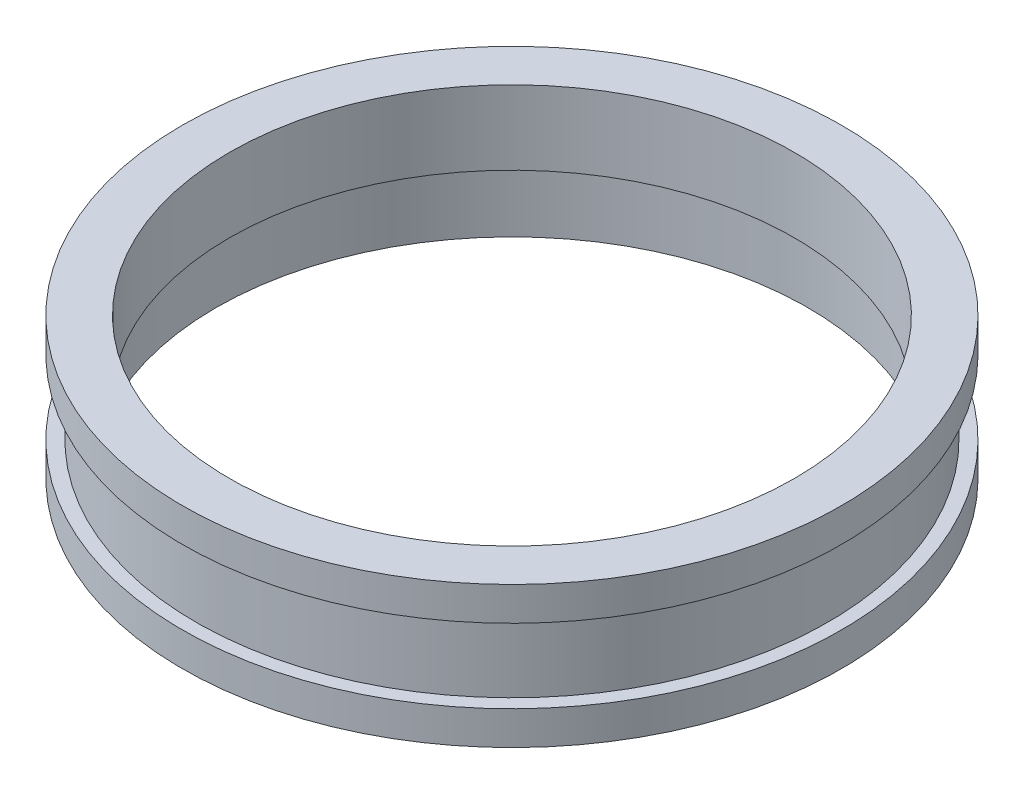
SolidWorks part; units mm, degrees
ref_plane "Front Plane" through (0, 0, 0) normal (0, 0, 1) x (1, 0, 0)
ref_plane "Top Plane" through (0, 0, 0) normal (0, 1, 0) x (1, 0, 0)
ref_plane "Right Plane" through (0, 0, 0) normal (1, 0, 0) x (0, 0, -1)
sketch "Sketch1" plane through (0, 0, 0) normal (0, 0, 1) x (1, 0, 0)
  line L11 (-49, 12) -> (-49, 17)
  line L12 (-49, 17) -> (-47, 17)
  line L13 (-47, 17) -> (-47, 28)
  line L14 (-47, 28) -> (-49, 28)
  line L15 (-49, 28) -> (-49, 33)
  line L16 (-49, 33) -> (-42, 33)
  line L17 (0, 15.8556) -> (0, -8.6801)
  line L18 (-44, 12) -> (-49, 12)
  line L19 (-44, 12) -> (-44, 22)
  line L20 (-44, 22) -> (-42, 22)
  line L21 (-42, 22) -> (-42, 33)
  dimension "D3" = 5
  dimension "D4" = 11
  dimension "D5" = 5
  dimension "D6" = 5
  dimension "D7" = 10
  dimension "D8" = 2
  dimension "D11" = 7
  dimension "D12" = 2
  dimension "D13" = 2
  dimension "D16" = 2
  dimension "D21" = 0
revolve "Revolve1" add sketch "Sketch1" angle 360 about L17
